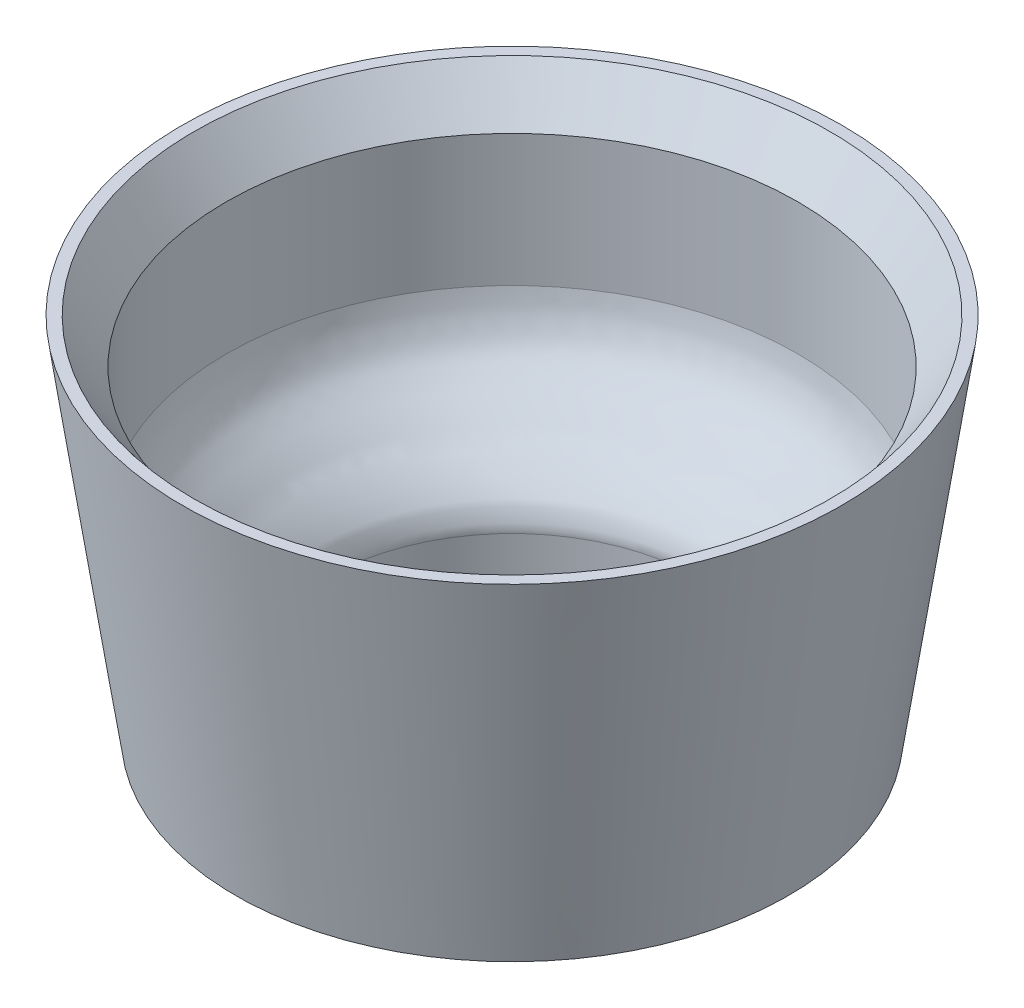
SolidWorks part; units mm, degrees
material "ABS PC"
ref_plane "Front Plane" through (0, 0, 0) normal (0, 0, 1) x (1, 0, 0)
ref_plane "Top Plane" through (0, 0, 0) normal (0, 1, 0) x (1, 0, 0)
ref_plane "Right Plane" through (0, 0, 0) normal (1, 0, 0) x (0, 0, -1)
sketch "Sketch1" plane through (0, 0, 0) normal (1, 0, 0) x (0, 0, -1)
  line L0 (26.0878, 274.978) -> (26.0878, 232.1195)
  line L2 (40.135, 299.274) -> (-40.135, 299.274) construction
  line L5 (0, 324) -> (3.2968, 324)
  line L8 (0, 324) -> (0, 0) construction
  line L9 (26.0878, 262.3641) -> (26.0878, 259.4973) construction
  line L12 (40.135, 302.9291) -> (40.135, 295.6188)
  line L16 (0, 0) -> (51.9362, 327.9125) construction
  line L17 (0, 324) -> (0, 332) construction
  line L18 (26.0878, 274.978) -> (26.0878, 268.978) construction
  line L19 (26.0878, 268.978) -> (26.0878, 248.978) construction
  line L20 (26.0878, 268.978) -> (42.6019, 268.978) construction
  line L21 (26.0878, 274.978) -> (43.5522, 274.978) construction
  line L22 (26.0878, 248.978) -> (39.4342, 248.978) construction
  line L23 (0, 0) -> (-51.9362, 327.9125) construction
  line L24 (-47.4003, 299.274) -> (-47.4003, 268.978) construction
  line L25 (-47.4003, 268.978) -> (-42.6019, 268.978) construction
  line L26 (0, 332) -> (0, 76.96) construction
  line L27 (0, 76.96) -> (400, 76.96) construction
  line L28 (0, 76.96) -> (-400, 76.96) construction
  line L29 (-200, 76.96) -> (-200, 183.96) construction
  line L30 (200, 76.96) -> (200, 183.96) construction
  line L31 (-200, 183.96) -> (-200, 182.57) construction
  line L32 (-200, 182.57) -> (400, 182.57) construction
  line L33 (-200, 182.57) -> (-400, 182.57) construction
  line L38 (0, 186.1152) -> (0, 324)
  line L39 (26.0878, 232.1195) -> (26.0878, 182.57) construction
  line L41 (21.6442, 226.0993) -> (26.0878, 226.0993)
  line L42 (26.0878, 226.0993) -> (26.0878, 186.1152)
  line L43 (26.0878, 186.1152) -> (0, 186.1152)
  line L44 (0, 0) -> (575.122, 0) construction
  arc A0 (-298.7691, 144.7791) -> (305.6579, 129.6043) centre (0, 0) cw construction
  spline S0 degree 3 poles (21.6442, 226.0993) (21.9584, 226.1509) (22.4049, 226.153) (22.896, 226.3321) (23.44, 226.7494) (24.2443, 227.2014) (25.0066, 227.9724) (25.5796, 228.9522) (25.8622, 230.393) (26.0228, 231.4436) (26.0878, 232.1195) knots 0 0 0 0 0.091924 0.112491 0.205673 0.333714 0.459267 0.602423 0.748839 1 1 1 1
  spline S1 degree 3 poles (3.2968, 324) (4.1972, 323.8396) (5.699, 323.816) (7.6935, 323.4297) (9.2722, 323.1563) (10.7507, 322.8538) (12.1816, 322.5577) (13.6372, 322.313) (14.8643, 321.9117) (15.9115, 321.5662) (16.81, 321.2491) (17.7339, 321.0149) (18.8379, 320.6416) (19.931, 320.1935) (21.0686, 319.6948) (22.141, 319.2627) (23.2156, 318.6856) (24.4371, 318.1163) (25.6762, 317.3518) (27.1066, 316.7518) (28.4318, 315.7832) (29.7322, 314.8939) (31.058, 313.93) (32.1959, 312.8581) (33.3378, 311.8503) (34.4539, 310.9646) (35.3895, 309.8867) (36.5078, 309.0949) (37.2942, 308.0208) (38.1233, 307.1238) (38.9048, 306.0961) (39.4724, 304.6349) (40.2774, 303.734) (40.135, 302.9291) knots 0 0 0 0 0.061585 0.100795 0.136831 0.1697 0.202569 0.235438 0.269088 0.289473 0.309858 0.333319 0.353706 0.388423 0.412965 0.437514 0.46634 0.495168 0.528354 0.564387 0.59925 0.638593 0.670824 0.709635 0.743897 0.773612 0.805519 0.839783 0.864953 0.89467 0.922395 0.951224 1 1 1 1
  spline S2 degree 3 poles (40.135, 295.6188) (39.9636, 294.7131) (39.7869, 293.3689) (39.1095, 291.6901) (38.6019, 290.4599) (37.8418, 289.2392) (36.9195, 288.2279) (35.9232, 287.2651) (34.974, 286.2515) (33.8311, 285.3463) (32.8233, 284.2966) (31.8701, 283.2868) (30.7668, 282.4387) (29.8742, 281.4644) (28.8604, 280.5152) (28.0567, 279.5119) (27.1438, 278.5569) (26.4968, 277.0287) (26.0081, 275.8567) (26.0878, 274.978) knots 0 0 0 0 0.108356 0.15601 0.210945 0.263562 0.322855 0.370186 0.4254 0.484692 0.539909 0.595126 0.646549 0.701764 0.749093 0.808384 0.85195 0.901837 1 1 1 1
  point P10 (0, 299.274)
  point P63 (0, 299.274)
  dimension "D3" = 9
  dimension "D1" = 40.135
  dimension "D2" = 324
  dimension "D4" = 8
  dimension "D5" = 3.2968
  dimension "D6" = 4.4435
  dimension "D7" = 6.0202
  dimension "D8" = 7.7403
  dimension "D9" = 6
  dimension "D10" = 20
  dimension "D11" = 9.317
  dimension "D12" = 10.7504
  dimension "D13" = 255.04
  dimension "D14" = 107
  dimension "D15" = 107
  dimension "D16" = 332
  dimension "D17" = 105.61
  dimension "D18" = 105.61
  dimension "D19" = 12.1838
  dimension "D20" = 13.6172
  dimension "D21" = 15.0506
  dimension "D22" = 15.9106
  dimension "D23" = 16.7707
  dimension "D24" = 17.7739
  dimension "D25" = 18.6341
  dimension "D26" = 20.0676
  dimension "D27" = 21.0708
  dimension "D28" = 22.0743
  dimension "D29" = 23.2209
  dimension "D30" = 24.3677
  dimension "D31" = 25.6578
  dimension "D32" = 27.0911
  dimension "D33" = 28.3811
  dimension "D34" = 29.8146
  dimension "D35" = 30.9613
  dimension "D36" = 32.2513
  dimension "D37" = 33.3981
  dimension "D38" = 34.4014
  dimension "D39" = 35.4048
  dimension "D40" = 36.5516
  dimension "D41" = 37.2681
  dimension "D42" = 38.1282
  dimension "D43" = 38.8449
  dimension "D44" = 39.4183
  dimension "D45" = 39.9917
  dimension "D46" = 323.8567
  dimension "D47" = 323.7133
  dimension "D48" = 323.4267
  dimension "D49" = 323.1399
  dimension "D50" = 322.8533
  dimension "D51" = 322.5666
  dimension "D52" = 322.2799
  dimension "D53" = 321.8499
  dimension "D54" = 321.5632
  dimension "D55" = 321.2765
  dimension "D56" = 320.9899
  dimension "D57" = 320.7031
  dimension "D58" = 320.1297
  dimension "D59" = 319.6998
  dimension "D60" = 319.2698
  dimension "D61" = 318.6965
  dimension "D62" = 318.1231
  dimension "D63" = 317.4064
  dimension "D64" = 316.6897
  dimension "D65" = 315.8296
  dimension "D66" = 314.8263
  dimension "D67" = 313.9663
  dimension "D68" = 312.8195
  dimension "D69" = 311.8162
  dimension "D70" = 310.9562
  dimension "D71" = 309.9528
  dimension "D72" = 308.9493
  dimension "D73" = 308.0893
  dimension "D74" = 307.086
  dimension "D75" = 306.0826
  dimension "D76" = 304.9359
  dimension "D77" = 303.9325
  dimension "D78" = 302.9291
sketch "Sketch2" plane through (0, 0, 0) normal (1, 0, 0) x (0, 0, -1)
  line L0 (0, 324) -> (3.2968, 324) construction
  line L1 (26.5078, 274.997) -> (26.5078, 268.8486)
  line L2 (40.5477, 295.5407) -> (40.5477, 314.2386)
  line L3 (40.135, 295.6188) -> (40.135, 302.9291) construction
  line L4 (40.135, 295.6188) -> (26.0878, 274.978) construction
  line L5 (0, 324.42) -> (3.4084, 324.42) construction
  line L6 (3.2968, 324) -> (40.135, 302.9291) construction
  line L7 (3.4084, 324.42) -> (40.555, 303.1727) construction
  line L8 (26.0878, 274.978) -> (26.0878, 232.1195) construction
  line L9 (40.555, 295.4895) -> (26.435, 274.7417) construction
  line L10 (0, 0) -> (0, 407.9498) construction
  line L12 (26.5078, 268.8486) -> (38.5078, 268.8486) construction
  line L13 (26.5078, 274.997) -> (26.5078, 232.1195) construction
  line L14 (38.5078, 268.8486) -> (46.4894, 323.5611) construction
  line L17 (40.5477, 314.2386) -> (45.93, 323.5611) construction
  line L18 (45.93, 323.5611) -> (46.4894, 323.5611) construction
  line L19 (0, 186.1152) -> (0, 324) construction
  line L20 (0, 324) -> (0, 332) construction
  line L21 (40.555, 295.4895) -> (40.555, 303.1727) construction
  line L22 (0, 0) -> (47.3115, 324.3086) construction
  line L23 (45.93, 323.5611) -> (47.2025, 323.5611) construction
  line L24 (47.2025, 323.5611) -> (39.2208, 268.8486) construction
  line L25 (39.2208, 268.8486) -> (26.5078, 268.8486)
  line L26 (44.1979, 320.5611) -> (46.7648, 320.5611)
  line L27 (44.1979, 320.5611) -> (40.5477, 314.2386)
  line L28 (46.7648, 320.5611) -> (39.2208, 268.8486)
  spline S0 degree 1 poles (40.5477, 295.5407) (26.5078, 274.997) knots 0 0 1 1 construction
  spline S1 degree 3 poles (40.135, 295.6188) (39.9636, 294.7131) (39.7869, 293.3689) (39.1095, 291.6901) (38.6019, 290.4599) (37.8418, 289.2392) (36.9195, 288.2279) (35.9232, 287.2651) (34.974, 286.2515) (33.8311, 285.3463) (32.8233, 284.2966) (31.8701, 283.2868) (30.7668, 282.4387) (29.8742, 281.4644) (28.8604, 280.5152) (28.0567, 279.5119) (27.1438, 278.5569) (26.4968, 277.0287) (26.0081, 275.8567) (26.0878, 274.978) knots 0 0 0 0 0.108356 0.15601 0.210945 0.263562 0.322855 0.370186 0.4254 0.484692 0.539909 0.595126 0.646549 0.701764 0.749093 0.808384 0.85195 0.901837 1 1 1 1 construction
  spline S2 degree 3 poles (40.5477, 295.5407) (40.4477, 295.0127) (40.2928, 293.9708) (39.9309, 292.5875) (39.5162, 291.5815) (39.1084, 290.578) (38.4397, 289.317) (37.3314, 288.0326) (36.3684, 287.1154) (35.6302, 286.3401) (35.0165, 285.7627) (34.3943, 285.2472) (33.6355, 284.5566) (32.9204, 283.7714) (32.1297, 282.9861) (31.4852, 282.4595) (30.915, 281.9635) (30.3717, 281.3913) (29.7828, 280.8046) (29.2276, 280.2622) (28.7248, 279.6749) (28.1804, 279.0397) (27.6518, 278.4702) (27.3081, 277.8768) (26.9952, 277.1272) (26.598, 276.1645) (26.4648, 275.4705) (26.5078, 274.997) knots 0 0 0 0 0.062544 0.125088 0.15636 0.187632 0.250176 0.31272 0.375264 0.406536 0.437808 0.46908 0.500352 0.562896 0.594168 0.62544 0.656713 0.687985 0.719257 0.750529 0.781801 0.813073 0.844345 0.875617 0.906889 0.938161 1.000705 1.000705 1.000705 1.000705
  point P38 (0, 328)
  dimension "D4" = 6.1484
  dimension "D5" = 8.3
  dimension "D6" = 30
  dimension "D7" = 45.93
  dimension "D8" = 45.39
  dimension "D9" = 8.3
  dimension "D10" = 40.5477
  dimension "D3" = 12
  dimension "D11" = 18.6979
  dimension "D12" = 3
  dimension "D1" = 0.42
  dimension "D2" = 0.42
revolve "Revolve6" add sketch "Sketch2" angle 360 about L10
sketch "Sketch3" plane through (0, 0, 0) normal (1, 0, 0) x (0, 0, -1)
  line L0 (44.1979, 320.5611) -> (40.5477, 314.2386) construction
  line L3 (46.7648, 320.5611) -> (-46.7648, 320.5611) construction
  line L4 (44.1979, 320.5611) -> (-44.1979, 320.5611) construction
  line L5 (40.5477, 314.2386) -> (-40.5477, 314.2386) construction
  line L6 (40.5477, 314.2386) -> (54.812, 333.8718)
  line L8 (54.812, 333.8718) -> (54.812, 347.837)
  line L9 (54.812, 347.837) -> (0, 347.837)
  line L10 (0, 347.837) -> (0, 311.6751)
  line L11 (0, 186.1152) -> (0, 324) construction
  line L12 (0, 311.6751) -> (40.5477, 311.6751)
  line L13 (40.5477, 311.6751) -> (40.5477, 314.2386)
  dimension "D1" = 36
  dimension "D2" = 54.812
revolve "Cut-Revolve1" cut sketch "Sketch3" angle 360 about L10
